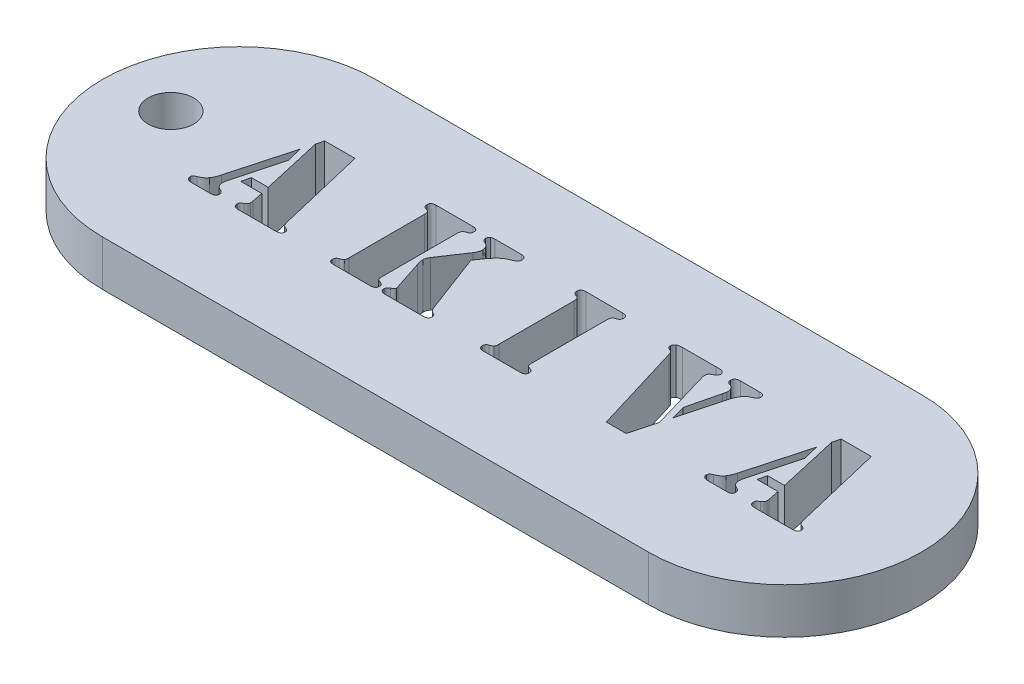
SolidWorks part; units mm, degrees
ref_plane "Front Plane" through (0, 0, 0) normal (0, 0, 1) x (1, 0, 0)
ref_plane "Top Plane" through (0, 0, 0) normal (0, 1, 0) x (1, 0, 0)
ref_plane "Right Plane" through (0, 0, 0) normal (1, 0, 0) x (0, 0, -1)
sketch "Sketch2" plane through (0, 0, 0) normal (0, 1, 0) x (1, 0, 0)
  line L0 (-30, 0) -> (30, 0) construction
  line L1 (-30, 15) -> (30, 15)
  line L2 (-30, -15) -> (30, -15)
  arc A0 (-30, 15) -> (-30, -15) centre (-30, 0) ccw
  arc A1 (30, -15) -> (30, 15) centre (30, 0) ccw
  text T0 "A K I V A " font "Stencil" height in points 48
  point P2 (0, 0)
  point P9 (-41.9782, -7.4)
  point P10 (-47.6198, -8.4415)
  point P11 (0, 0)
  point P12 (-50.6575, -8.9623)
  point P13 (-48.4009, -9.3963)
  point P14 (-40, 0)
  point P15 (41.6867, -5.8107)
  point P16 (-12.9065, -4.3687)
  point P17 (-17.595, -2.4524)
  point P18 (-15.7317, -3.1389)
  point P19 (-17.1, -2.9717)
  point P20 (-15.1993, -2.547)
  point P21 (-16.1344, -3.3729)
  point P22 (0, 0)
  point P23 (-15.3856, -2.5618)
  point P24 (-24.8799, -5.4615)
  point P25 (-28.9275, -7.4065)
  point P26 (-29.4532, -4.4628)
  point P27 (-31.0827, -5.4615)
  point P28 (-30.925, -4.9359)
  dimension "D1" = 30
  dimension "D2" = 60
extrude "Boss-Extrude1" add sketch "Sketch2" along normal blind 5
sketch "Sketch3" plane through (0, 5, 0) normal (0, 1, 0) x (1, 0, 0)
  circle A0 centre (-38.2317, 0.7413) radius 2.5
  point P2 (-61.9802, 1.2601)
  point P3 (-59.3674, 0.5182)
  point P4 (-23.0515, 0.624)
  point P5 (-65.8339, 1.4208)
  point P6 (-38.2317, 0.7413)
  dimension "D1" = 5
extrude "Cut-Extrude1" cut sketch "Sketch3" against normal blind 8
